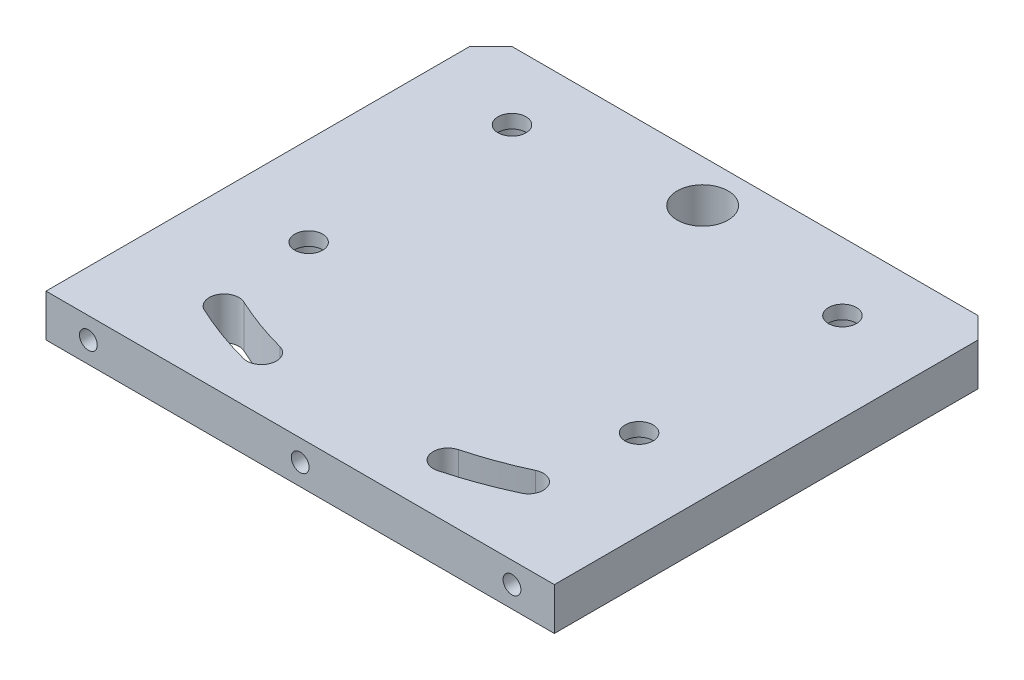
SolidWorks part; units mm, degrees
material "45#"
ref_plane "前视" through (0, 0, 0) normal (0, 0, 1) x (1, 0, 0)
ref_plane "上视" through (0, 0, 0) normal (0, 1, 0) x (1, 0, 0)
ref_plane "右视" through (0, 0, 0) normal (1, 0, 0) x (0, 0, -1)
sketch "草图1" plane through (0, 0, 0) normal (0, 1, 0) x (1, 0, 0)
  line L1 (-60, -52.5) -> (60, -52.5)
  line L2 (-60, -52.5) -> (-60, 52.5)
  line L3 (-60, 52.5) -> (60, 52.5)
  line L4 (60, -52.5) -> (60, 52.5)
  line L5 (-60, -52.5) -> (60, 52.5) construction
  line L6 (-60, 52.5) -> (60, -52.5) construction
  point P0 (0, 0)
  dimension "D1" = 120
  dimension "D2" = 105
extrude "凸台-拉伸1" add sketch "草图1" along normal blind 10
hole_wizard "打孔尺寸根据内六角圆柱头螺钉的类型1" positions "草图3" profile "草图2" counterbore size "M6" standard "Gb" end condition through all
sketch "草图3" plane through (0, 0, 0) normal (0, -1, 0) x (-1, 0, 0)
  line L0 (0, -52.5) -> (0, 12.5) construction
  line L1 (60, -52.5) -> (-60, -52.5) construction
  line L2 (0, 12.5) -> (-60, 12.5) construction
  line L4 (-60, 52.5) -> (60, 52.5) construction
  point P0 (39, -11.5)
  point P13 (-39, -11.5)
  point P14 (-39, 36.5)
  point P15 (39, 36.5)
  dimension "D1" = 48
  dimension "D2" = 78
  dimension "D3" = 40
sketch "草图2" plane through (-39, 0, 11.5) normal (1, 0, 0) x (0, 0, -1)
  line L0 (0, 0) -> (0, 10)
  line L1 (0, 10) -> (3.3, 10)
  line L3 (3.3, 10) -> (3.3, 6.8)
  line L4 (3.3, 6.8) -> (5.5, 6.8)
  line L5 (5.5, 6.8) -> (5.5, 0)
  line L7 (5.5, 0) -> (0, 0)
  line L11 (0, -6.35) -> (0, 107.95) construction
  dimension "通孔孔直径" = 6.6
  dimension "通孔孔深度" = 10
  dimension "柱形沉头孔直径" = 11
  dimension "柱形沉头孔深度" = 6.8
hole_wizard "孔1" positions "草图6" profile "草图5" legacy end condition through all
sketch "草图6" plane through (0, 10, 0) normal (0, 1, 0) x (1, 0, 0)
  line L0 (0, 52.5) -> (0, 29.325) construction
  line L1 (60, 52.5) -> (-60, 52.5) construction
  point P0 (0, 42.5)
  dimension "D1" = 10
sketch "草图5" plane through (0, 10, -42.5) normal (1, 0, 0) x (0, 0, 1)
  line L0 (0, 0) -> (0, 10)
  line L1 (0, 10) -> (6, 10)
  line L2 (6, 10) -> (6, 0)
  line L3 (6, 0) -> (0, 0)
  line L4 (0, 110) -> (0, -10) construction
  dimension "直径" = 12
  dimension "深度" = 10
sketch "草图7" plane through (0, 10, 0) normal (0, 1, 0) x (1, 0, 0)
  line L0 (0, 42.5) -> (-34.5772, -52.5) construction
  line L1 (0, 42.5) -> (-37.4017, -37.7082) construction
  line L2 (0, 42.5) -> (-22.9055, -42.9844) construction
  line L4 (-60, -52.5) -> (60, -52.5) construction
  line L6 (0, 42.5) -> (0, -64.9143) construction
  arc A0 (-37.4017, -37.7082) -> (-22.9055, -42.9844) centre (0, 42.5) ccw
  circle A1 centre (0, 42.5) radius 85 construction
  arc A2 (-34.4434, -31.3641) -> (-21.0938, -36.223) centre (0, 42.5) ccw
  arc A3 (-21.0938, -36.223) -> (-22.9055, -42.9844) centre (-21.9996, -39.6037) cw
  arc A4 (-34.4434, -31.3641) -> (-37.4017, -37.7082) centre (-35.9226, -34.5362) ccw
  arc A5 (34.4434, -31.3641) -> (37.4017, -37.7082) centre (35.9226, -34.5362) cw
  arc A6 (21.0938, -36.223) -> (22.9055, -42.9844) centre (21.9996, -39.6037) ccw
  arc A7 (34.4434, -31.3641) -> (21.0938, -36.223) centre (0, 42.5) cw
  arc A8 (37.4017, -37.7082) -> (22.9055, -42.9844) centre (0, 42.5) cw
  dimension "D3" = 170
  dimension "D1" = 10
  dimension "D2" = 7
  dimension "D4" = 20
extrude "切除-拉伸2" cut sketch "草图7" against normal up to next
hole_wizard "M5 螺纹孔1" positions "草图9" profile "草图8" tap size "M5" standard "Gb"
sketch "草图9" plane through (-19.2703, 3.1384, 52.5) normal (0, 0, -1) x (1, 0, 0)
  line L0 (19.2703, 45) -> (19.2703, 26.866) construction
  line L2 (-30.7297, -1.8616) -> (-40.7297, -1.8616) construction
  line L3 (-40.7297, -6.8616) -> (-40.7297, 3.1384) construction
  point P0 (-30.7297, -1.8616)
  point P9 (69.2703, -1.8616)
  point P13 (19.2703, -1.8616)
  dimension "D1" = 100
cosmetic thread "孔螺蚊线1"
cosmetic thread "孔螺蚊线2"
cosmetic thread "孔螺蚊线3"
sketch "草图8" plane through (-50, 5, 52.5) normal (1, 0, 0) x (0, -1, 0)
  line L0 (0, 0) -> (0, 11.6618)
  line L1 (0, 11.6618) -> (2.1, 10.4)
  line L2 (2.1, 10.4) -> (2.1, 0)
  line L5 (2.1, 0) -> (0, 0)
  line L10 (0, 11.6618) -> (-2.1, 10.4) construction
  line L11 (0, -6.35) -> (0, 107.95) construction
  dimension "螺纹孔钻头直径" = 4.2
  dimension "螺纹孔钻头深度" = 10.4
  dimension "导头角度" = 118
chamfer "倒角1" distance 5 angle 45 2 edges at (-60, 5, -52.5) (60, 5, -52.5)
